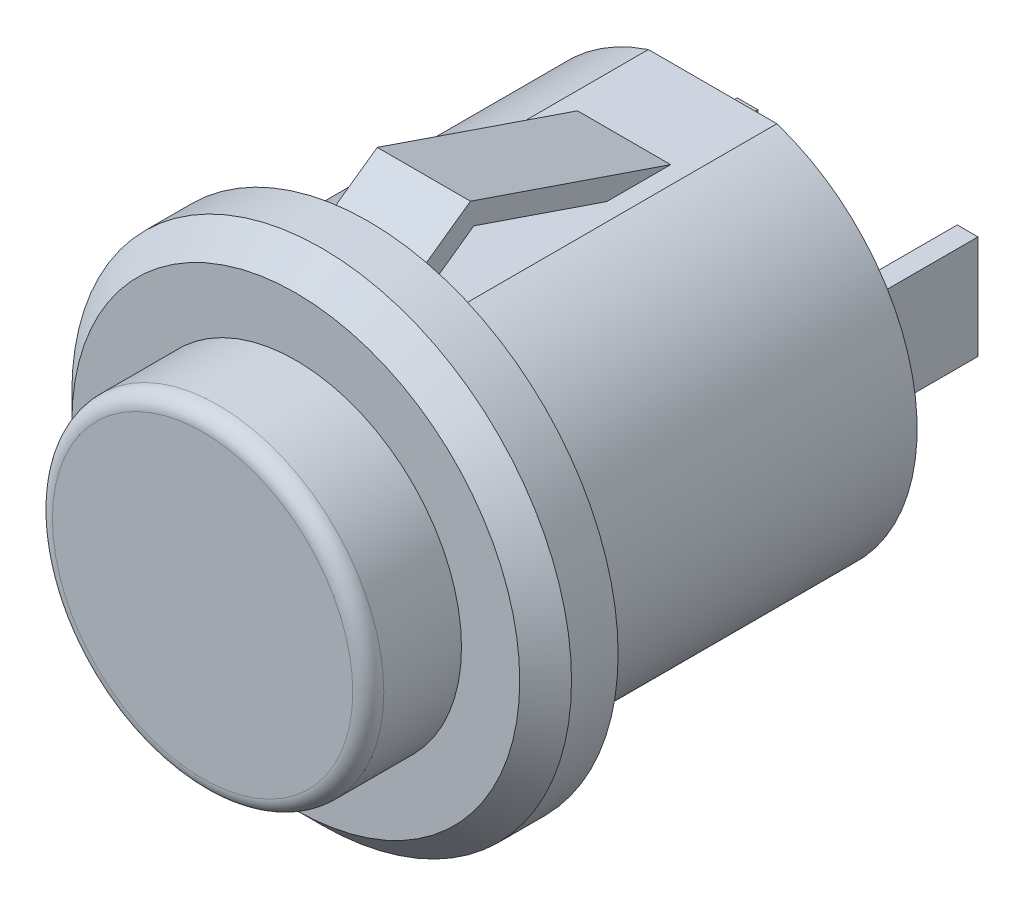
SolidWorks part; units mm, degrees
ref_plane "Front Plane" through (0, 0, 0) normal (0, 0, 1) x (1, 0, 0)
ref_plane "Top Plane" through (0, 0, 0) normal (0, 1, 0) x (1, 0, 0)
ref_plane "Right Plane" through (0, 0, 0) normal (1, 0, 0) x (0, 0, -1)
sketch "Sketch1" plane through (0, 0, 0) normal (0, 0, 1) x (1, 0, 0)
  circle A0 centre (0, 0) radius 9.65
  dimension "D1" = 19.3
extrude "Boss-Extrude1" add sketch "Sketch1" along normal blind 2.8
chamfer "Chamfer1" distance 1 angle 45 1 edges at (9.65, 0, 2.8)
sketch "Sketch2" plane through (0, 0, 2.8) normal (0, 0, 1) x (1, 0, 0)
  circle A0 centre (0, 0) radius 6.4
  dimension "D1" = 12.8
extrude "Boss-Extrude2" add sketch "Sketch2" along normal blind 3.6
fillet "Fillet1" radius 0.6 1 edges at (6.4, 0, 6.4)
sketch "Sketch3" plane through (0, 0, 0) normal (0, 0, -1) x (-1, 0, 0)
  circle A0 centre (0, 0) radius 7.9
  dimension "D1" = 15.8
extrude "Boss-Extrude3" add sketch "Sketch3" along normal blind 13.3
sketch "Sketch6" plane through (0, 0, -13.3) normal (0, 0, -1) x (-1, 0, 0)
  line L0 (-7.9, 0) -> (7.9, 0) construction
  line L1 (0, -7.9) -> (0, 7.9) construction
  line L2 (-2.4819, 7.5) -> (2.4819, 7.5)
  line L3 (-2.4819, -7.5) -> (2.4819, -7.5)
  circle A0 centre (0, 0) radius 7.9 construction
  circle A1 centre (0, 0) radius 7.9
  point P9 (0, 7.5)
  circle M4 centre (0, 0) radius 7.9
  dimension "D1" = 7.5
extrude "Cut-Extrude1" cut sketch "Sketch6" against normal up to surface (13.3 mm away) contours L2 M4 | L3 M4 up to face at (-7.9, 0, 0)
sketch "Sketch4" plane through (0, 0, -13.3) normal (0, 0, -1) x (-1, 0, 0)
  line L0 (0, 7.9) -> (0, -7.9) construction
  line L1 (-7.9, 0) -> (7.9, 0) construction
  line L2 (4.65, -2) -> (3.85, -2)
  line L3 (-4.65, 2) -> (-3.85, 2)
  line L4 (-4.65, 2) -> (-4.65, -2)
  line L5 (-4.65, -2) -> (-3.85, -2)
  line L6 (-3.85, 2) -> (-3.85, -2)
  line L7 (-4.65, 2) -> (-3.85, -2) construction
  line L8 (-4.65, -2) -> (-3.85, 2) construction
  line L9 (3.85, 2) -> (3.85, -2)
  line L10 (4.65, 2) -> (3.85, 2)
  line L11 (4.65, 2) -> (4.65, -2)
  circle A0 centre (0, 0) radius 7.9 construction
  circle A1 centre (0, 0) radius 7.9 construction
  point P9 (-4.25, 0)
  dimension "D1" = 4.25
  dimension "D2" = 4
  dimension "D3" = 0.8
extrude "Boss-Extrude4" add sketch "Sketch4" along normal blind 5.6
sketch "Sketch8" plane through (0, 0, 0) normal (1, 0, 0) x (0, 0, -1)
  line L0 (-0.8878, -7.5) -> (2.2106, -9.7)
  line L1 (2.2106, -9.7) -> (8.6449, -7.5)
  line L2 (0, -7.5) -> (13.3, -7.5) construction
  line L3 (0, -8.621) -> (2.1461, -10.1448)
  line L4 (2.1461, -10.1448) -> (9.8812, -7.5)
  line L5 (-0.1969, -7.5) -> (2.2751, -9.2552)
  line L6 (2.2751, -9.2552) -> (7.4085, -7.5)
  line L7 (-0.8878, -7.5) -> (13.3, -7.5)
  line L8 (-1.1194, -7.8261) -> (2.1461, -10.1448) construction
  line L9 (0, -9.65) -> (0, 9.65)
  line L10 (0, -9.65) -> (0, 9.65) construction
  line L11 (2.2751, -9.2552) -> (8.5154, -7.1215) construction
  line L12 (2.1461, -10.1448) -> (8.7743, -7.8785) construction
  line L13 (-0.6562, -7.1739) -> (2.2751, -9.2552) construction
  point P12 (0, -8.015)
  point P18 (8.1562, -7.5)
  point P20 (10.438, -7.5)
  point P22 (0.6346, -7.5)
  point P24 (0, 0)
  point P25 (-0.1457, -7.5)
  point P27 (-0.4156, -7.5)
  point P28 (-0.8878, -7.5)
  dimension "D1" = 2.2
  dimension "D2" = 3.8
  dimension "D3" = 6.8
  dimension "D4" = 0.4
  dimension "D5" = 0.4
extrude "Boss-Extrude6" add sketch "Sketch8" along normal blind 1.8 and the other way blind 1.8 contours L9 L3 L4 L7 L1 L0 | L7 L0 L1 L6 L5
pattern_circular "CirPattern1" count 2 over 360 about axis through (0, 0, -13.3) along (0, 0, 1) of "Boss-Extrude6"
